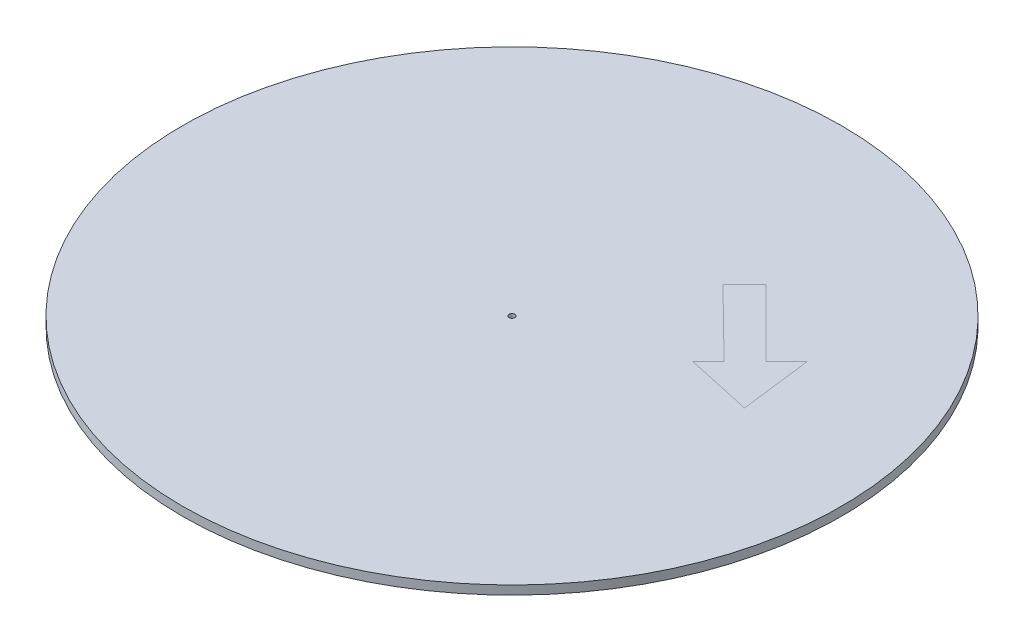
SolidWorks part; units mm, degrees
material "ABS"
ref_plane "Alzado" through (0, 0, 0) normal (0, 0, 1) x (1, 0, 0)
ref_plane "Planta" through (0, 0, 0) normal (0, 1, 0) x (1, 0, 0)
ref_plane "Vista lateral" through (0, 0, 0) normal (1, 0, 0) x (0, 0, -1)
sketch "Croquis2" plane through (0, 0, 0) normal (0, 1, 0) x (1, 0, 0)
  line L1 (-120, 120) -> (120, 120) construction
  line L2 (-120, 120) -> (-120, -120) construction
  line L3 (-120, -120) -> (120, -120) construction
  line L4 (120, 120) -> (120, -120) construction
  line L5 (-120, 120) -> (120, -120) construction
  line L6 (-120, -120) -> (120, 120) construction
  circle A0 centre (0, 0) radius 112.5
  point P0 (0, 0)
  dimension "D3" = 225
  dimension "D1" = 240
  dimension "D2" = 240
extrude "Saliente-Extruir1" add sketch "Croquis2" along normal blind 3
sketch "Croquis3" plane through (0, 3, 0) normal (0, 1, 0) x (1, 0, 0)
  circle A0 centre (0, 0) radius 1
  dimension "D1" = 2
extrude "Cortar-Extruir1" cut sketch "Croquis3" against normal up to next
sketch "Croquis4" plane through (0, 3, 0) normal (0, 1, 0) x (1, 0, 0)
  line L0 (26.6711, 45.3409) -> (34.0449, 52.7147)
  line L1 (34.0449, 52.7147) -> (56.7938, 29.9658)
  line L2 (56.7938, 29.9658) -> (63.8538, 37.0258)
  line L3 (63.8538, 37.0258) -> (66.9131, 12.4727)
  line L4 (66.9131, 12.4727) -> (44.2427, 17.4147)
  line L5 (44.2427, 17.4147) -> (49.6121, 22.7841)
  line L6 (49.6121, 22.7841) -> (26.6711, 45.3409)
extrude "Cortar-Extruir2" cut sketch "Croquis4" against normal blind 0.1
